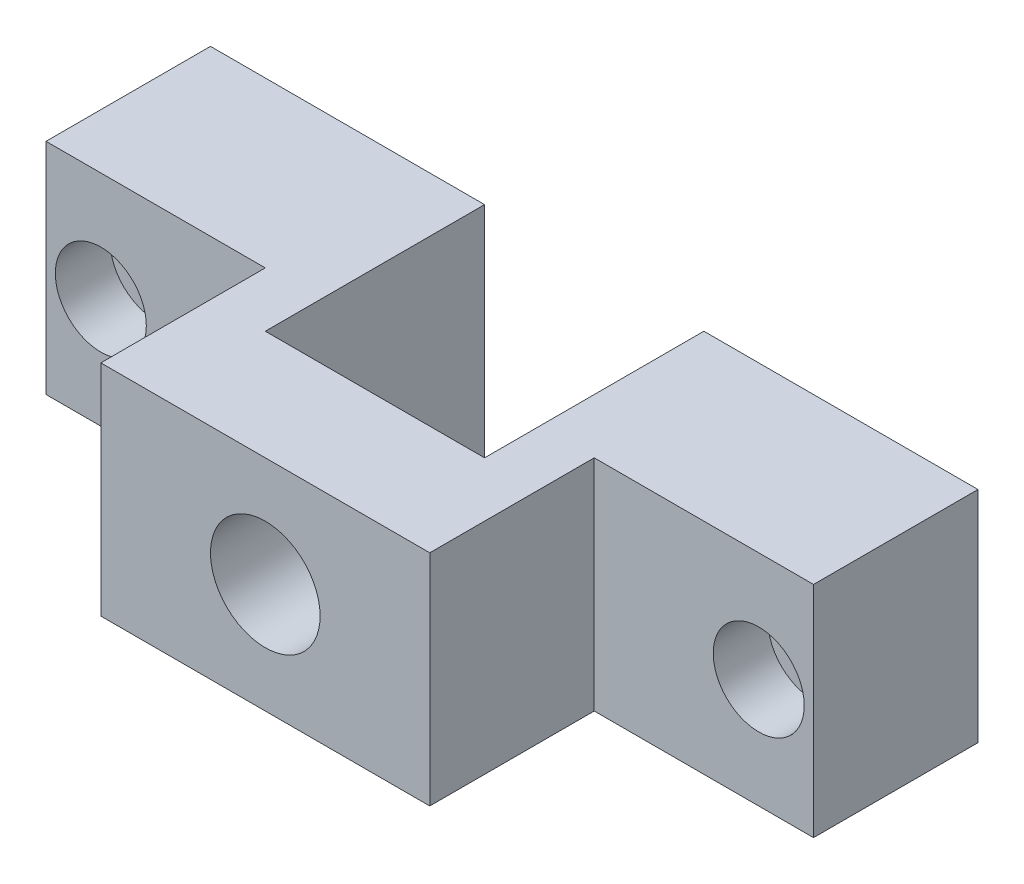
SolidWorks part; units mm, degrees
ref_plane "Front Plane" through (0, 0, 0) normal (0, 0, 1) x (1, 0, 0)
ref_plane "Top Plane" through (0, 0, 0) normal (0, 1, 0) x (1, 0, 0)
ref_plane "Right Plane" through (0, 0, 0) normal (1, 0, 0) x (0, 0, -1)
sketch "Sketch1" plane through (0, 0, 0) normal (0, 0, 1) x (1, 0, 0)
  line L1 (0, 0) -> (70, 0)
  line L2 (0, 0) -> (0, 20)
  line L3 (0, 20) -> (70, 20)
  line L4 (70, 0) -> (70, 20)
  circle A1 centre (65, 10) radius 2.5
  circle A2 centre (5, 10) radius 2.5
  dimension "D1" = 70
  dimension "D2" = 20
extrude "Boss-Extrude1" add sketch "Sketch1" along normal blind 15
sketch "Sketch2" plane through (0, 0, 15) normal (0, 0, 1) x (1, 0, 0)
  line L0 (0, 0) -> (70, 0) construction
  line L1 (20, 0) -> (50, 0)
  line L2 (20, 0) -> (20, 20)
  line L3 (20, 20) -> (50, 20)
  line L4 (50, 0) -> (50, 20)
  line L5 (70, 20) -> (0, 20) construction
extrude "Boss-Extrude2" add sketch "Sketch2" along normal blind 15
sketch "Sketch4" plane through (0, 20, 0) normal (0, 1, 0) x (1, 0, 0)
  line L0 (70, 0) -> (0, 0) construction
  line L1 (25, -20) -> (45, -20)
  line L2 (25, -20) -> (25, 0)
  line L3 (25, 0) -> (45, 0)
  line L4 (45, -20) -> (45, 0)
extrude "Cut-Extrude1" cut sketch "Sketch4" against normal through all
sketch "Sketch5" plane through (0, 0, 30) normal (0, 0, 1) x (1, 0, 0)
  circle A0 centre (35, 10) radius 5
  circle A1 centre (65, 10) radius 2.5 construction
  dimension "D1" = 30
extrude "Cut-Extrude2" cut sketch "Sketch5" against normal through all
sketch "Sketch6" plane through (0, 0, 15) normal (0, 0, 1) x (1, 0, 0)
  circle A0 centre (5, 10) radius 4.15
extrude "Cut-Extrude3" cut sketch "Sketch6" against normal blind 5
sketch "Sketch7" plane through (0, 0, 15) normal (0, 0, 1) x (1, 0, 0)
  circle A0 centre (65, 10) radius 4.15
extrude "Cut-Extrude4" cut sketch "Sketch7" against normal blind 5
